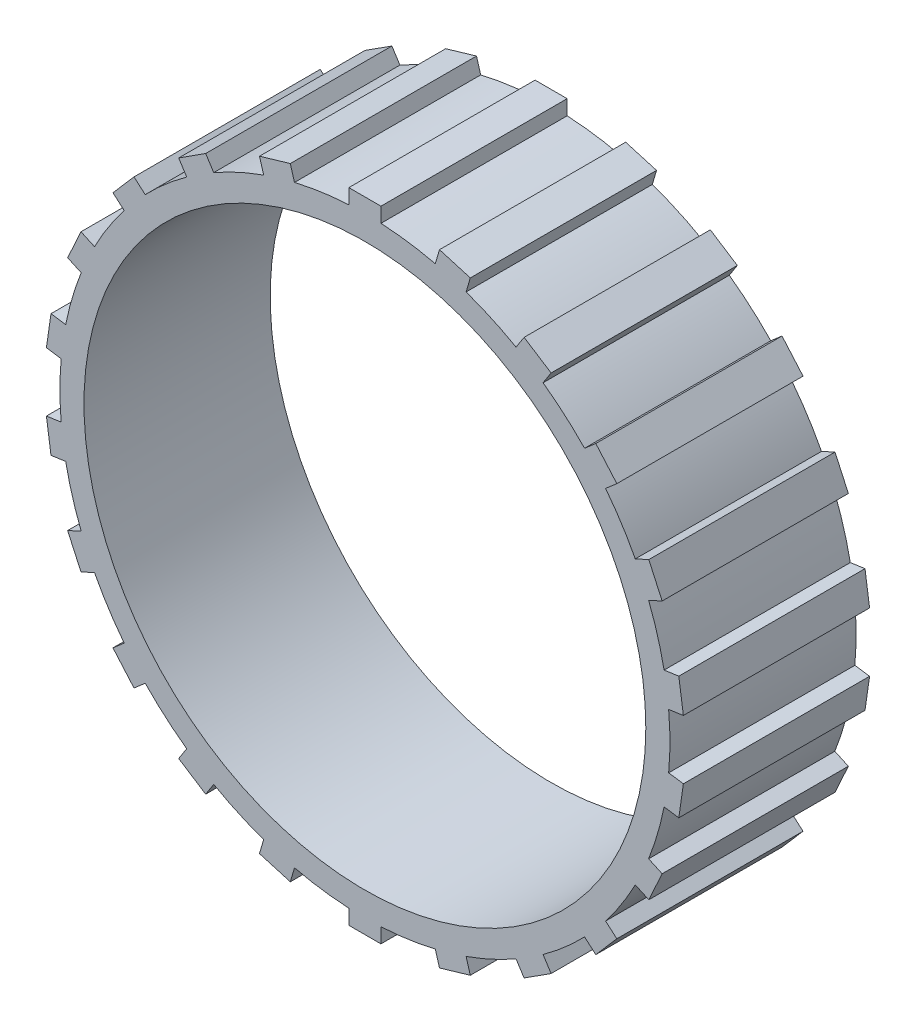
SolidWorks part; units mm, degrees
ref_plane "Front Plane" through (0, 0, 0) normal (0, 0, 1) x (1, 0, 0)
ref_plane "Top Plane" through (0, 0, 0) normal (0, 1, 0) x (1, 0, 0)
ref_plane "Right Plane" through (0, 0, 0) normal (1, 0, 0) x (0, 0, -1)
sketch "Sketch1" plane through (0, 0, 0) normal (0, 0, 1) x (1, 0, 0)
  circle A0 centre (-43.2127, 1.4419) radius 9.5
  dimension "D1" = 19
extrude "Boss-Extrude1" add sketch "Sketch1" along normal blind 5.8
sketch "Sketch2" plane through (0, 0, 5.8) normal (0, 0, 1) x (1, 0, 0)
  circle A0 centre (-43.2127, 1.4419) radius 8.75
  dimension "D1" = 17.5
extrude "Cut-Extrude1" cut sketch "Sketch2" against normal blind 5.8
sketch "Sketch3" plane through (0, 0, 5.8) normal (0, 0, 1) x (1, 0, 0)
  line L0 (-40.8892, 11.1297) -> (-39.9297, 10.848)
  line L1 (-43.7127, 11.3919) -> (-42.7127, 11.3919)
  line L2 (-43.7127, 11.3919) -> (-43.7127, 10.3919)
  line L3 (-43.7127, 10.3919) -> (-42.7127, 10.3919)
  line L4 (-42.7127, 11.3919) -> (-42.7127, 10.3919)
  line L5 (-40.8892, 11.1297) -> (-41.1709, 10.1702)
  line L6 (-41.1709, 10.1702) -> (-40.2114, 9.8885)
  line L7 (-39.9297, 10.848) -> (-40.2114, 9.8885)
  line L8 (-38.2539, 10.0827) -> (-37.4127, 9.542)
  line L9 (-38.2539, 10.0827) -> (-38.7946, 9.2414)
  line L10 (-38.7946, 9.2414) -> (-37.9533, 8.7008)
  line L11 (-37.4127, 9.542) -> (-37.9533, 8.7008)
  line L12 (-36.0204, 8.3356) -> (-35.3655, 7.5799)
  line L13 (-36.0204, 8.3356) -> (-36.7761, 7.6807)
  line L14 (-36.7761, 7.6807) -> (-36.1213, 6.925)
  line L15 (-35.3655, 7.5799) -> (-36.1213, 6.925)
  line L16 (-34.3695, 6.0301) -> (-33.9541, 5.1204)
  line L17 (-34.3695, 6.0301) -> (-35.2792, 5.6146)
  line L18 (-35.2792, 5.6146) -> (-34.8638, 4.705)
  line L19 (-33.9541, 5.1204) -> (-34.8638, 4.705)
  line L20 (-33.4351, 3.3528) -> (-33.2928, 2.363)
  line L21 (-33.4351, 3.3528) -> (-34.4249, 3.2105)
  line L22 (-34.4249, 3.2105) -> (-34.2826, 2.2207)
  line L23 (-33.2928, 2.363) -> (-34.2826, 2.2207)
  line L24 (-33.2928, 0.5207) -> (-33.4351, -0.4691)
  line L25 (-33.2928, 0.5207) -> (-34.2826, 0.6631)
  line L26 (-34.2826, 0.6631) -> (-34.4249, -0.3268)
  line L27 (-33.4351, -0.4691) -> (-34.4249, -0.3268)
  line L28 (-33.9541, -2.2367) -> (-34.3695, -3.1463)
  line L29 (-33.9541, -2.2367) -> (-34.8638, -1.8213)
  line L30 (-34.8638, -1.8213) -> (-35.2792, -2.7309)
  line L31 (-34.3695, -3.1463) -> (-35.2792, -2.7309)
  line L32 (-35.3655, -4.6961) -> (-36.0204, -5.4519)
  line L33 (-35.3655, -4.6961) -> (-36.1213, -4.0413)
  line L34 (-36.1213, -4.0413) -> (-36.7761, -4.797)
  line L35 (-36.0204, -5.4519) -> (-36.7761, -4.797)
  line L36 (-37.4127, -6.6583) -> (-38.2539, -7.1989)
  line L37 (-37.4127, -6.6583) -> (-37.9533, -5.817)
  line L38 (-37.9533, -5.817) -> (-38.7946, -6.3577)
  line L39 (-38.2539, -7.1989) -> (-38.7946, -6.3577)
  line L40 (-39.9297, -7.9642) -> (-40.8892, -8.246)
  line L41 (-39.9297, -7.9642) -> (-40.2114, -7.0047)
  line L42 (-40.2114, -7.0047) -> (-41.1709, -7.2865)
  line L43 (-40.8892, -8.246) -> (-41.1709, -7.2865)
  line L44 (-42.7127, -8.5081) -> (-43.7127, -8.5081)
  line L45 (-42.7127, -8.5081) -> (-42.7127, -7.5081)
  line L46 (-42.7127, -7.5081) -> (-43.7127, -7.5081)
  line L47 (-43.7127, -8.5081) -> (-43.7127, -7.5081)
  line L48 (-45.5362, -8.246) -> (-46.4957, -7.9642)
  line L49 (-45.5362, -8.246) -> (-45.2544, -7.2865)
  line L50 (-45.2544, -7.2865) -> (-46.2139, -7.0047)
  line L51 (-46.4957, -7.9642) -> (-46.2139, -7.0047)
  line L52 (-48.1714, -7.1989) -> (-49.0127, -6.6583)
  line L53 (-48.1714, -7.1989) -> (-47.6308, -6.3577)
  line L54 (-47.6308, -6.3577) -> (-48.472, -5.817)
  line L55 (-49.0127, -6.6583) -> (-48.472, -5.817)
  line L56 (-50.4049, -5.4519) -> (-51.0598, -4.6961)
  line L57 (-50.4049, -5.4519) -> (-49.6492, -4.797)
  line L58 (-49.6492, -4.797) -> (-50.3041, -4.0413)
  line L59 (-51.0598, -4.6961) -> (-50.3041, -4.0413)
  line L60 (-52.0558, -3.1463) -> (-52.4712, -2.2367)
  line L61 (-52.0558, -3.1463) -> (-51.1462, -2.7309)
  line L62 (-51.1462, -2.7309) -> (-51.5616, -1.8213)
  line L63 (-52.4712, -2.2367) -> (-51.5616, -1.8213)
  line L64 (-52.9902, -0.4691) -> (-53.1325, 0.5207)
  line L65 (-52.9902, -0.4691) -> (-52.0004, -0.3268)
  line L66 (-52.0004, -0.3268) -> (-52.1427, 0.6631)
  line L67 (-53.1325, 0.5207) -> (-52.1427, 0.6631)
  line L68 (-53.1325, 2.363) -> (-52.9902, 3.3528)
  line L69 (-53.1325, 2.363) -> (-52.1427, 2.2207)
  line L70 (-52.1427, 2.2207) -> (-52.0004, 3.2105)
  line L71 (-52.9902, 3.3528) -> (-52.0004, 3.2105)
  line L72 (-52.4712, 5.1204) -> (-52.0558, 6.0301)
  line L73 (-52.4712, 5.1204) -> (-51.5616, 4.705)
  line L74 (-51.5616, 4.705) -> (-51.1462, 5.6146)
  line L75 (-52.0558, 6.0301) -> (-51.1462, 5.6146)
  line L76 (-51.0598, 7.5799) -> (-50.4049, 8.3356)
  line L77 (-51.0598, 7.5799) -> (-50.3041, 6.925)
  line L78 (-50.3041, 6.925) -> (-49.6492, 7.6807)
  line L79 (-50.4049, 8.3356) -> (-49.6492, 7.6807)
  line L80 (-49.0127, 9.542) -> (-48.1714, 10.0827)
  line L81 (-49.0127, 9.542) -> (-48.472, 8.7008)
  line L82 (-48.472, 8.7008) -> (-47.6308, 9.2414)
  line L83 (-48.1714, 10.0827) -> (-47.6308, 9.2414)
  line L84 (-46.4957, 10.848) -> (-45.5362, 11.1297)
  line L85 (-46.4957, 10.848) -> (-46.2139, 9.8885)
  line L86 (-46.2139, 9.8885) -> (-45.2544, 10.1702)
  line L87 (-45.5362, 11.1297) -> (-45.2544, 10.1702)
  circle A0 centre (-43.2127, 1.4419) radius 8.75 construction
  point P93 (-43.2127, 1.4419)
  dimension "D1" = 1
  dimension "D2" = 0.5
  dimension "D3" = 8.95
  dimension "D4" = 1
  dimension "D5" = 22
extrude "Boss-Extrude2" add sketch "Sketch3" against normal up to surface (5.8 mm away) up to face at (-34.4627, 1.4419, 0)
